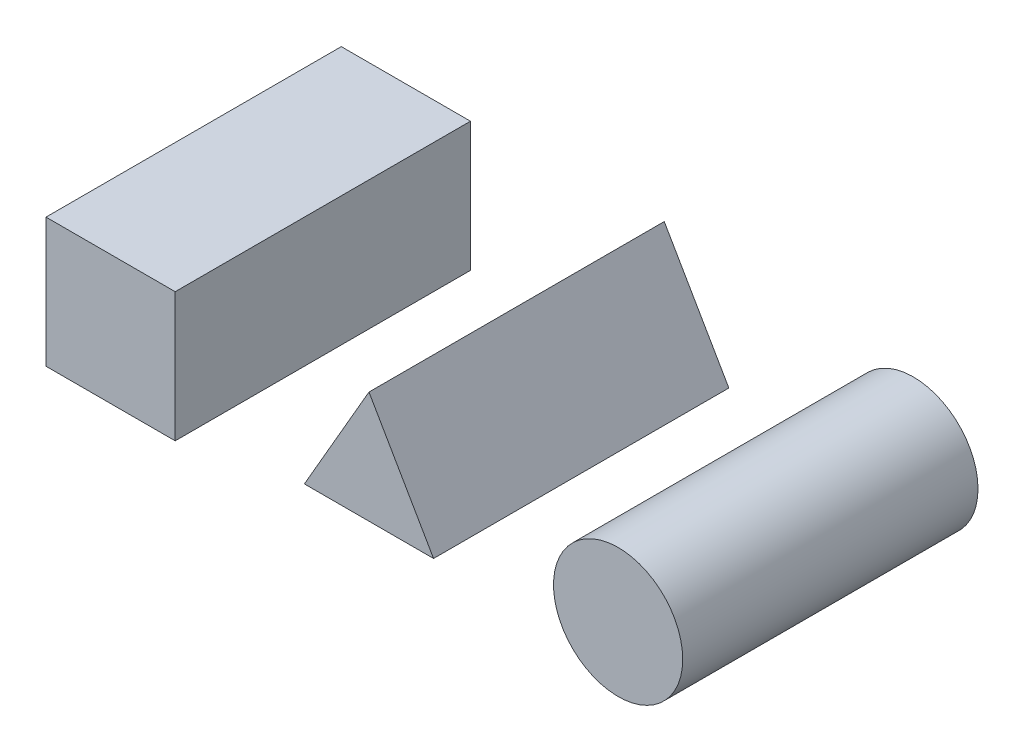
SolidWorks part; units mm, degrees
ref_plane "Front Plane" through (0, 0, 0) normal (0, 0, 1) x (1, 0, 0)
ref_plane "Top Plane" through (0, 0, 0) normal (0, 1, 0) x (1, 0, 0)
ref_plane "Right Plane" through (0, 0, 0) normal (1, 0, 0) x (0, 0, -1)
sketch "Sketch1" plane through (0, 0, 0) normal (0, 0, 1) x (1, 0, 0)
  line L0 (-117.5, 0) -> (117.5, 0) construction
  line L1 (-117.5, 55) -> (117.5, 55)
  line L2 (-117.5, 55) -> (-117.5, -55)
  line L3 (-117.5, -55) -> (117.5, -55)
  line L4 (117.5, 55) -> (117.5, -55)
  line L5 (0, 55) -> (0, -55) construction
  line L6 (-17.5, -10.1036) -> (0, 20.2073)
  line L7 (-87.5, 17.5) -> (-52.5, 17.5)
  line L8 (-87.5, 17.5) -> (-87.5, -17.5)
  line L9 (-87.5, -17.5) -> (-52.5, -17.5)
  line L10 (-52.5, 17.5) -> (-52.5, -17.5)
  line L11 (-87.5, 17.5) -> (-52.5, -17.5) construction
  line L12 (-87.5, -17.5) -> (-52.5, 17.5) construction
  line L14 (-1.3522, 0) -> (0, -1.3522)
  line L18 (0, 20.2073) -> (17.5, -10.1036)
  line L19 (17.5, -10.1036) -> (-17.5, -10.1036)
  line L20 (-17.5, -10.1036) -> (8.75, 5.0518) construction
  line L21 (17.5, -10.1036) -> (-8.75, 5.0518) construction
  line L22 (0, 20.2073) -> (0, 0) construction
  circle A0 centre (67.5, 0) radius 17.5
  point P10 (-70, 0)
  point P20 (0, 0)
  point P27 (7.7505, -5.3087)
  point P28 (0, 0)
  dimension "D2" = 50
  dimension "cylinder" = 35
  dimension "D1" = 30
  dimension "square2" = 35
  dimension "square" = 35
  dimension "triangle3" = 35
  dimension "triangle2" = 35
  dimension "triangle" = 35
extrude "Boss-Extrude1" add sketch "Sketch1" along normal blind 80
